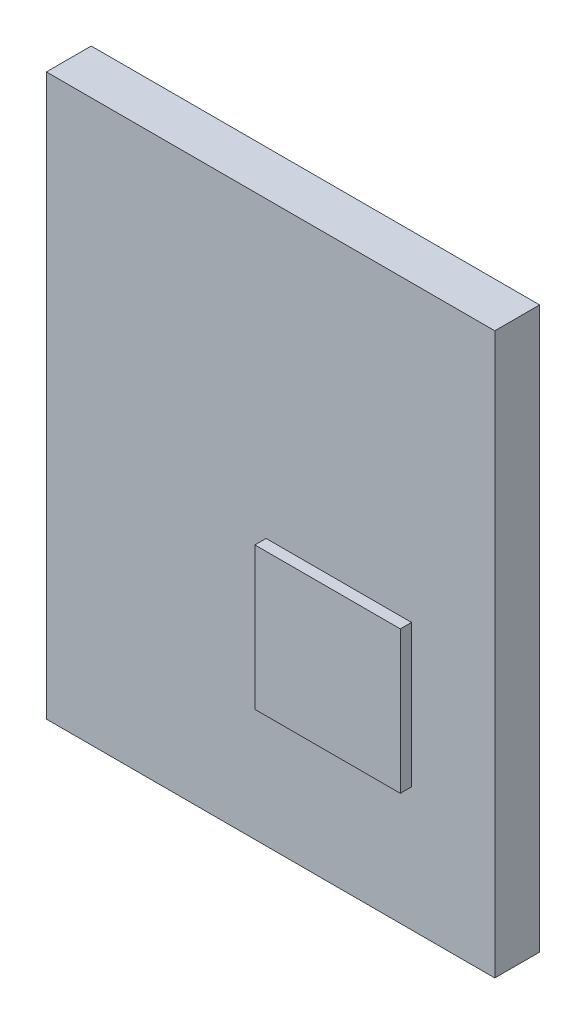
SolidWorks part; units mm, degrees
ref_plane "前视基准面" through (0, 0, 0) normal (0, 0, 1) x (1, 0, 0)
ref_plane "上视基准面" through (0, 0, 0) normal (0, 1, 0) x (1, 0, 0)
ref_plane "右视基准面" through (0, 0, 0) normal (1, 0, 0) x (0, 0, -1)
sketch "草图1" plane through (0, 0, 0) normal (0, 0, 1) x (1, 0, 0)
  line L1 (10, -12.5) -> (-10, -12.5)
  line L2 (10, -12.5) -> (10, 12.5)
  line L3 (10, 12.5) -> (-10, 12.5)
  line L4 (-10, -12.5) -> (-10, 12.5)
  line L5 (10, -12.5) -> (-10, 12.5) construction
  line L6 (10, 12.5) -> (-10, -12.5) construction
  point P0 (0, 0)
  dimension "D1" = 20
  dimension "D2" = 25
extrude "凸台-拉伸1" add sketch "草图1" along normal blind 2
sketch "草图2" plane through (0, 0, 2) normal (0, 0, 1) x (1, 0, 0)
  line L1 (-0.2014, -0.6211) -> (6.2853, -0.6211)
  line L2 (-0.2014, -0.6211) -> (-0.2014, -6.9733)
  line L3 (-0.2014, -6.9733) -> (6.2853, -6.9733)
  line L4 (6.2853, -0.6211) -> (6.2853, -6.9733)
  line L5 (-0.2014, -0.6211) -> (6.2853, -6.9733) construction
  line L6 (-0.2014, -6.9733) -> (6.2853, -0.6211) construction
  point P0 (3.0419, -3.7972)
extrude "凸台-拉伸2" add sketch "草图2" along normal blind 0.5
